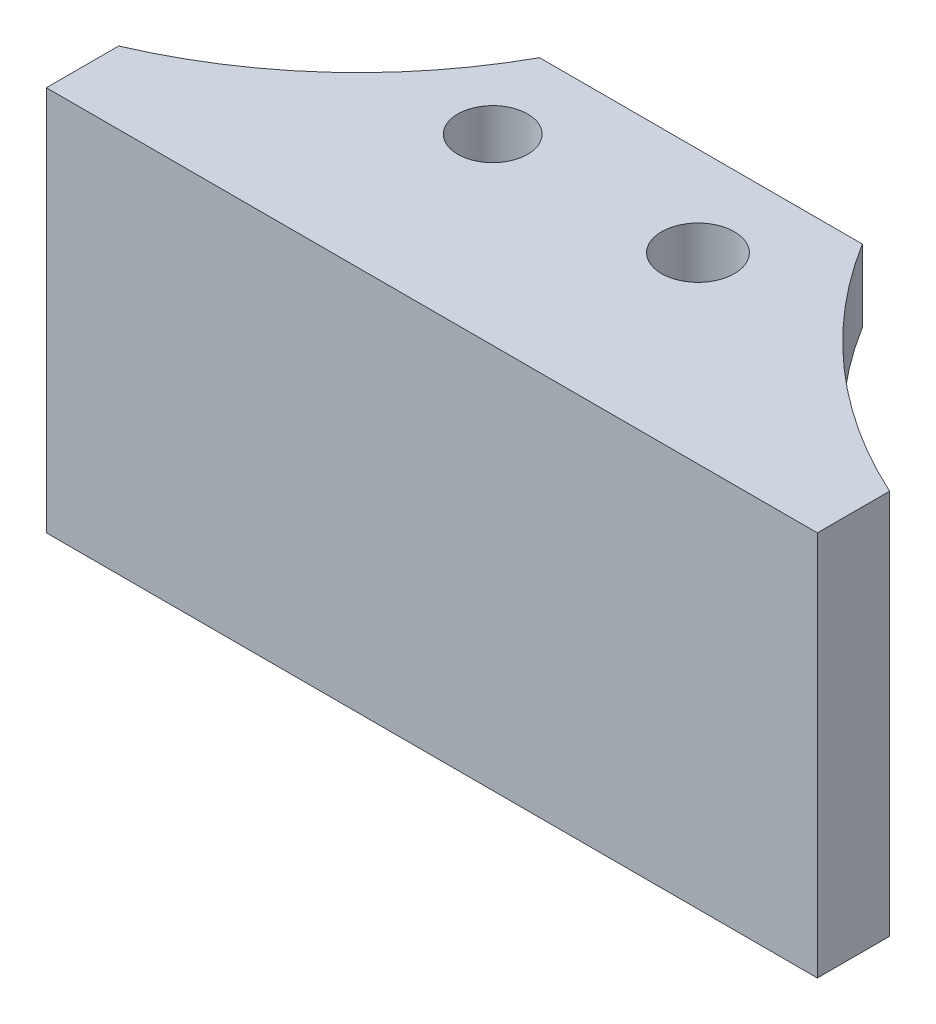
SolidWorks part; units mm, degrees
ref_plane "Front Plane" through (0, 0, 0) normal (0, 0, 1) x (1, 0, 0)
ref_plane "Top Plane" through (0, 0, 0) normal (0, 1, 0) x (1, 0, 0)
ref_plane "Right Plane" through (0, 0, 0) normal (1, 0, 0) x (0, 0, -1)
sketch "Sketch1" plane through (0, 0, 0) normal (0, 0, 1) x (1, 0, 0)
  line L1 (0, 0) -> (160, 0)
  line L2 (0, 0) -> (0, 80)
  line L3 (0, 80) -> (160, 80)
  line L4 (160, 0) -> (160, 80)
  dimension "D1" = 160
  dimension "D2" = 80
extrude "Boss-Extrude1" add sketch "Sketch1" along normal blind 15 contours L2 L1 L4 L3
sketch "Sketch2" plane through (0, 80, 0) normal (0, 1, 0) x (1, 0, 0)
  line L0 (45.7788, 41.5755) -> (112.7657, 41.5755)
  arc A0 (0, 0) -> (45.7788, 41.5755) centre (-37.4103, 87.1838) ccw
  arc A1 (112.7657, 41.5755) -> (160, 0) centre (204.7149, 98.4206) ccw
  circle A3 centre (54.6533, 22.9699) radius 7.2554
  circle A4 centre (97.2573, 22.9699) radius 7.5501
  line M4 (160, 0) -> (0, 0)
extrude "Boss-Extrude2" add sketch "Sketch2" against normal blind 15 contours A1 L0 A0 A4 A3 M4
